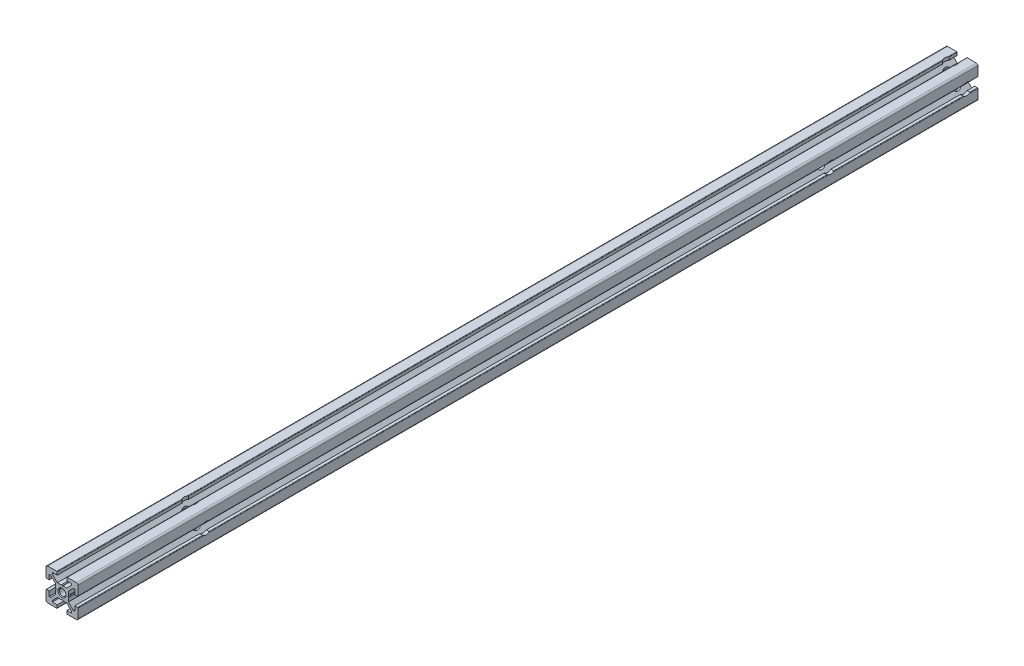
SolidWorks part; units mm, degrees
material "6063-T5"
ref_plane "Front Plane" through (0, 0, 0) normal (0, 0, 1) x (1, 0, 0)
ref_plane "Top Plane" through (0, 0, 0) normal (0, 1, 0) x (1, 0, 0)
ref_plane "Right Plane" through (0, 0, 0) normal (1, 0, 0) x (0, 0, -1)
ref_plane "Plane1" through (0, 0, 0) normal (0, 0, 1) x (1, 0, 0)
sketch "Sketch1" plane through (0, 0, 0) normal (0, 0, 1) x (1, 0, 0)
  line L0 (-10, 9) -> (-10, 3.3)
  line L1 (-9.7, 3) -> (-8, 3)
  line L2 (-8, 3) -> (-8, 6)
  line L3 (-8, 6) -> (-7.0607, 6)
  line L4 (-7.0607, 6) -> (-4, 2.9393)
  line L5 (-4, 2.9393) -> (-4, 0.5196)
  line L6 (-4, 0.5196) -> (-3.7, 0)
  line L7 (-3.7, 0) -> (-4, -0.5196)
  line L8 (-4, -0.5196) -> (-4, -2.9393)
  line L9 (-4, -2.9393) -> (-7.0607, -6)
  line L10 (-7.0607, -6) -> (-8, -6)
  line L11 (-8, -6) -> (-8, -3)
  line L12 (-8, -3) -> (-9.7, -3)
  line L13 (-10, -3.3) -> (-10, -9)
  line L14 (-9, -10) -> (-3.3, -10)
  line L15 (-3, -9.7) -> (-3, -8)
  line L16 (-3, -8) -> (-6, -8)
  line L17 (-6, -8) -> (-6, -7.0607)
  line L18 (-6, -7.0607) -> (-2.9393, -4)
  line L19 (-2.9393, -4) -> (-0.5196, -4)
  line L20 (-0.5196, -4) -> (0, -3.7)
  line L21 (0, -3.7) -> (0.5196, -4)
  line L22 (0.5196, -4) -> (2.9393, -4)
  line L23 (2.9393, -4) -> (6, -7.0607)
  line L24 (6, -7.0607) -> (6, -8)
  line L25 (6, -8) -> (3, -8)
  line L26 (3, -8) -> (3, -9.7)
  line L27 (3.3, -10) -> (9, -10)
  line L28 (10, -9) -> (10, -3.3)
  line L29 (9.7, -3) -> (8, -3)
  line L30 (8, -3) -> (8, -6)
  line L31 (8, -6) -> (7.0606, -6)
  line L32 (7.0606, -6) -> (4, -2.9393)
  line L33 (4, -2.9393) -> (4, -0.5196)
  line L34 (4, -0.5196) -> (3.7, 0)
  line L35 (3.7, 0) -> (4, 0.5196)
  line L36 (4, 0.5196) -> (4, 2.9393)
  line L37 (4, 2.9393) -> (7.0607, 6)
  line L38 (7.0607, 6) -> (8, 6)
  line L39 (8, 6) -> (8, 3)
  line L40 (8, 3) -> (9.7, 3)
  line L41 (10, 3.3) -> (10, 9)
  line L42 (9, 10) -> (3.3, 10)
  line L43 (3, 9.7) -> (3, 8)
  line L44 (3, 8) -> (6, 8)
  line L45 (6, 8) -> (6, 7.0607)
  line L46 (6, 7.0607) -> (2.9393, 4)
  line L47 (2.9393, 4) -> (0.5196, 4)
  line L48 (0.5196, 4) -> (0, 3.7)
  line L49 (0, 3.7) -> (-0.5196, 4)
  line L50 (-0.5196, 4) -> (-2.9394, 4)
  line L51 (-2.9394, 4) -> (-6, 7.0606)
  line L52 (-6, 7.0606) -> (-6, 8)
  line L53 (-6, 8) -> (-3, 8)
  line L54 (-3, 8) -> (-3, 9.7)
  line L55 (-3.3, 10) -> (-9, 10)
  arc A0 (-10, 3.3) -> (-9.7, 3) centre (-9.7, 3.3) ccw
  arc A1 (-9.7, -3) -> (-10, -3.3) centre (-9.7, -3.3) ccw
  arc A2 (-10, -9) -> (-9, -10) centre (-9, -9) ccw
  arc A3 (-3.3, -10) -> (-3, -9.7) centre (-3.3, -9.7) ccw
  arc A4 (3, -9.7) -> (3.3, -10) centre (3.3, -9.7) ccw
  arc A5 (9, -10) -> (10, -9) centre (9, -9) ccw
  arc A6 (10, -3.3) -> (9.7, -3) centre (9.7, -3.3) ccw
  arc A7 (9.7, 3) -> (10, 3.3) centre (9.7, 3.3) ccw
  arc A8 (10, 9) -> (9, 10) centre (9, 9) ccw
  arc A9 (3.3, 10) -> (3, 9.7) centre (3.3, 9.7) ccw
  arc A10 (-3, 9.7) -> (-3.3, 10) centre (-3.3, 9.7) ccw
  arc A11 (-9, 10) -> (-10, 9) centre (-9, 9) ccw
extrude "Boss-Extrude1" add sketch "Sketch1" against normal blind 562
ref_plane "Plane2" through (0, 0, 0) normal (1, 0, 0) x (0, 0, -1)
sketch "Sketch2" plane through (0, 0, 0) normal (1, 0, 0) x (0, 0, -1)
  line L0 (0, 0) -> (0, 2.5)
  line L1 (0, 2.5) -> (0.433, 2.067)
  line L2 (0.433, 2.067) -> (562, 2.067)
  line L3 (562, 2.067) -> (562, 0)
  line L4 (562, 0) -> (0, 0)
  line L5 (562, 0) -> (0, 0) construction
revolve "Cut-Revolve1" cut sketch "Sketch2" angle 360 about L5
cosmetic thread "Cosmetic Thread1" parameters "D1"=15, "D2"=5
ref_plane "Plane3" through (0, 0, 0) normal (1, 0, 0) x (0, 0, -1)
sketch "Sketch3" plane through (0, 0, 0) normal (1, 0, 0) x (0, 0, -1)
  circle A0 centre (555, 0) radius 3.675
extrude "Cut-Extrude1" cut sketch "Sketch3" against normal blind 10 and the other way blind 10
ref_plane "Plane4" through (0, 0, 0) normal (0, 1, 0) x (1, 0, 0)
sketch "Sketch4" plane through (0, 0, 0) normal (0, 1, 0) x (1, 0, 0)
  circle A0 centre (0, 555) radius 3.675
extrude "Cut-Extrude2" cut sketch "Sketch4" against normal blind 10 and the other way blind 10
ref_plane "Plane5" through (0, 0, 0) normal (1, 0, 0) x (0, 0, -1)
sketch "Sketch5" plane through (0, 0, 0) normal (1, 0, 0) x (0, 0, -1)
  circle A0 centre (470, 0) radius 3.6751
extrude "Cut-Extrude3" cut sketch "Sketch5" against normal blind 10 and the other way blind 10
ref_plane "Plane6" through (0, 0, 0) normal (1, 0, 0) x (0, 0, -1)
sketch "Sketch6" plane through (0, 0, 0) normal (1, 0, 0) x (0, 0, -1)
  line L1 (466.3249, 0) -> (0, 0) construction
  circle A0 centre (80, 0) radius 3.6752
  dimension "D1" = 80
  dimension "D2" = 7.3504
extrude "Cut-Extrude4" cut sketch "Sketch6" against normal blind 10 and the other way blind 10
ref_plane "Plane7" through (0, 0, 0) normal (0, 1, 0) x (1, 0, 0)
sketch "Sketch7" plane through (0, 0, 0) normal (0, 1, 0) x (1, 0, 0)
  line L0 (0, 551.325) -> (0, 0) construction
  circle A0 centre (0, 80) radius 3.6752
  dimension "D1" = 7.3504
  dimension "D2" = 80
extrude "Cut-Extrude5" cut sketch "Sketch7" against normal blind 10 and the other way blind 10
